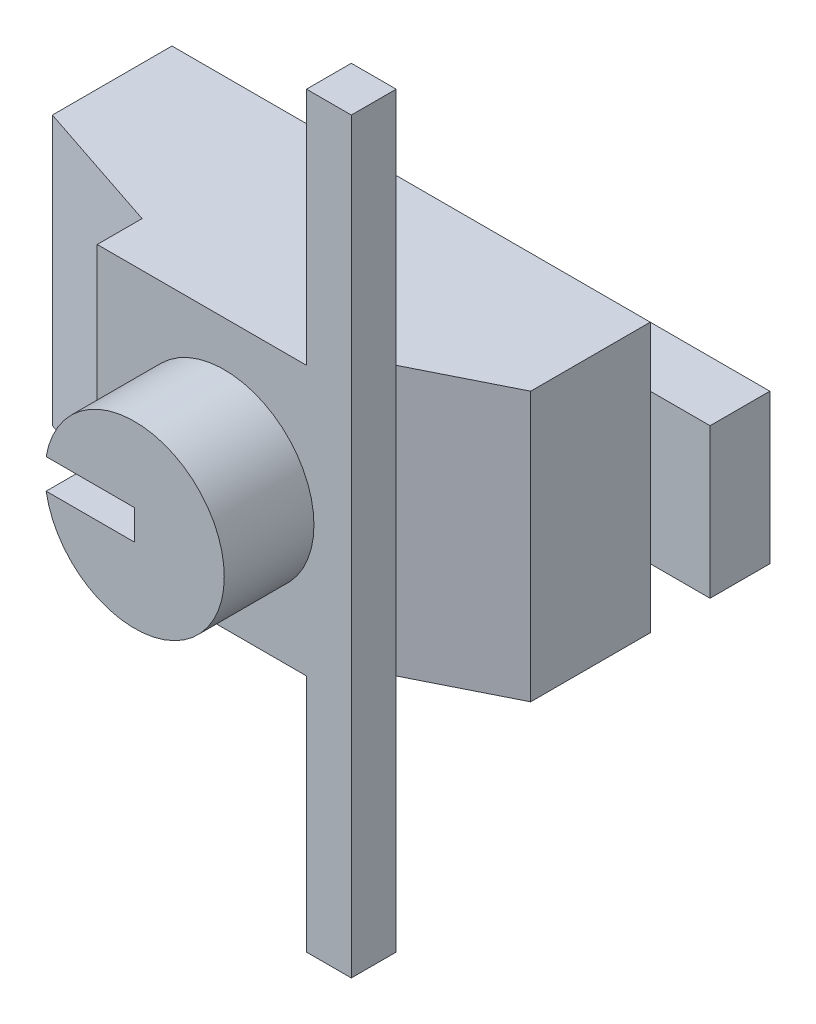
SolidWorks part; units mm, degrees
ref_plane "Спереди" through (0, 0, 0) normal (0, 0, 1) x (1, 0, 0)
ref_plane "Сверху" through (0, 0, 0) normal (0, 1, 0) x (1, 0, 0)
ref_plane "Справа" through (0, 0, 0) normal (1, 0, 0) x (0, 0, -1)
sketch "Эскиз1" plane through (0, 0, 0) normal (0, 0, 1) x (1, 0, 0)
  line L1 (0, 0) -> (200, 0)
  line L2 (0, 0) -> (0, -50)
  line L3 (0, -50) -> (200, -50)
  line L4 (200, 0) -> (200, -50)
  dimension "D1" = 200
  dimension "D2" = 50
extrude "Бобышка-Вытянуть1" add sketch "Эскиз1" along normal blind 20
sketch "Эскиз2" plane through (0, 0, 20) normal (0, 0, 1) x (1, 0, 0)
  line L0 (0, -50) -> (200, -50) construction
  line L1 (20, 20) -> (180, 20)
  line L2 (20, 20) -> (20, -70)
  line L3 (20, -70) -> (180, -70)
  line L4 (180, 20) -> (180, -70)
  point P4 (0, 0)
  point P6 (189.6891, -60.8969)
  point P7 (180, -0.181)
  dimension "D1" = 20
  dimension "D2" = 20
  dimension "D3" = 20
  dimension "D4" = 20
extrude "Бобышка-Вытянуть2" add sketch "Эскиз2" along normal blind 40
sketch "Эскиз3" plane through (0, -70, 0) normal (0, -1, 0) x (1, 0, 0)
  line L0 (20, 60) -> (65, 75)
  line L1 (65, 75) -> (65, 60)
  line L2 (20, 60) -> (180, 60) construction
  line L3 (65, 60) -> (65, 90)
  line L4 (65, 90) -> (135, 90)
  line L5 (135, 90) -> (135, 60)
  line L6 (135, 60) -> (65, 60)
  line L7 (20, 60) -> (65, 60)
  line L8 (150, 75) -> (180, 60)
  line L9 (135, 90) -> (150, 90)
  line L10 (135, 90) -> (135, 75)
  line L11 (135, 75) -> (150, 75)
  line L12 (150, 90) -> (150, 75)
  line L13 (180, 60) -> (135, 60)
  line L14 (135, 60) -> (135, 75)
  line L15 (150, 75) -> (180, 60)
  point P3 (0, 0)
  point P13 (0, 0)
  line M11 (180, 60) -> (20, 60)
  dimension "D1" = 70
  dimension "D2" = 30
  dimension "D3" = 15
  dimension "D4" = 45
  dimension "D5" = 15
  dimension "D6" = 15
extrude "Бобышка-Вытянуть3" add sketch "Эскиз3" against normal blind 90 contours L5 L4 L3 L1 M11 | L12 L9 L5 L11 | L11 L5 L8 M11 | L1 L0 M11
sketch "Эскиз5" plane through (0, 20, 0) normal (0, 1, 0) x (1, 0, 0)
  line L1 (150, -90) -> (135, -90)
  line L2 (150, -90) -> (150, -75)
  line L3 (150, -75) -> (135, -75)
  line L4 (135, -90) -> (135, -75)
  dimension "D1" = 15
  dimension "D2" = 15
extrude "Бобышка-Вытянуть4" add sketch "Эскиз5" along normal mid plane 250 from offset 45 offset against normal yes
sketch "Эскиз6" plane through (0, 0, 90) normal (0, 0, 1) x (1, 0, 0)
  line L0 (65, -25) -> (150, -25) construction
  line L1 (65, 20) -> (65, -70) construction
  line L2 (150, 100) -> (150, -150) construction
  line L3 (107.5, 20) -> (107.5, -70) construction
  line L4 (65, 20) -> (135, 20) construction
  line L5 (65, -70) -> (135, -70) construction
  circle A0 centre (107.5, -25) radius 30
  dimension "D1" = 60
extrude "Бобышка-Вытянуть5" add sketch "Эскиз6" along normal blind 30
sketch "Эскиз7" plane through (0, 0, 120) normal (0, 0, 1) x (1, 0, 0)
  line L1 (107.5, -25) -> (77.5, -25)
  line L2 (107.5, -25) -> (107.5, -20)
  line L3 (107.5, -20) -> (77.5, -20)
  line L4 (77.5, -25) -> (77.5, -20)
  line L5 (107.5, -25) -> (77.5, -25)
  line L6 (107.5, -25) -> (107.5, -30)
  line L7 (107.5, -30) -> (77.5, -30)
  line L8 (77.5, -25) -> (77.5, -30)
  point P13 (0, 0)
  point P14 (0, 0)
  point P15 (78.1926, -25)
  point P16 (0, 0)
  point P17 (79.9971, -36.983)
  dimension "D1" = 5
  dimension "D2" = 5
  dimension "D3" = 30
  dimension "D4" = 5
  dimension "D6" = 30
extrude "Вырез-Вытянуть2" cut sketch "Эскиз7" against normal blind 30 contours L7 L6 L1 | L2 L3 L6 L1
